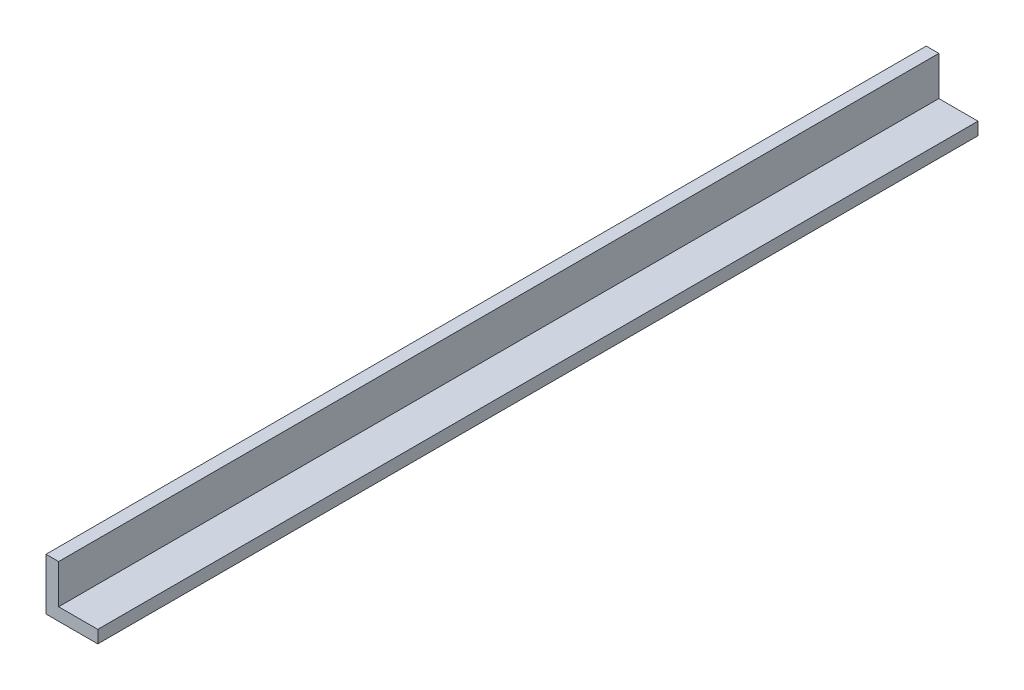
SolidWorks part; units mm, degrees
material "AISI Type 316L stainless steel"
ref_plane "Front Plane" through (0, 0, 0) normal (0, 0, 1) x (1, 0, 0)
ref_plane "Top Plane" through (0, 0, 0) normal (0, 1, 0) x (1, 0, 0)
ref_plane "Right Plane" through (0, 0, 0) normal (1, 0, 0) x (0, 0, -1)
sketch "Sketch1" plane through (0, 0, 0) normal (0, 0, 1) x (1, 0, 0)
  line L0 (0, 0) -> (12.7, 0)
  line L1 (12.7, 0) -> (12.7, 3.0988)
  line L2 (12.7, 3.0988) -> (3.0988, 3.0988)
  line L3 (3.0988, 3.0988) -> (3.0988, 12.7)
  line L4 (3.0988, 12.7) -> (0, 12.7)
  line L5 (0, 12.7) -> (0, 0)
  dimension "D1" = 12.7
  dimension "D2" = 3.0988
extrude "Boss-Extrude1" add sketch "Sketch1" along normal blind 215.9
